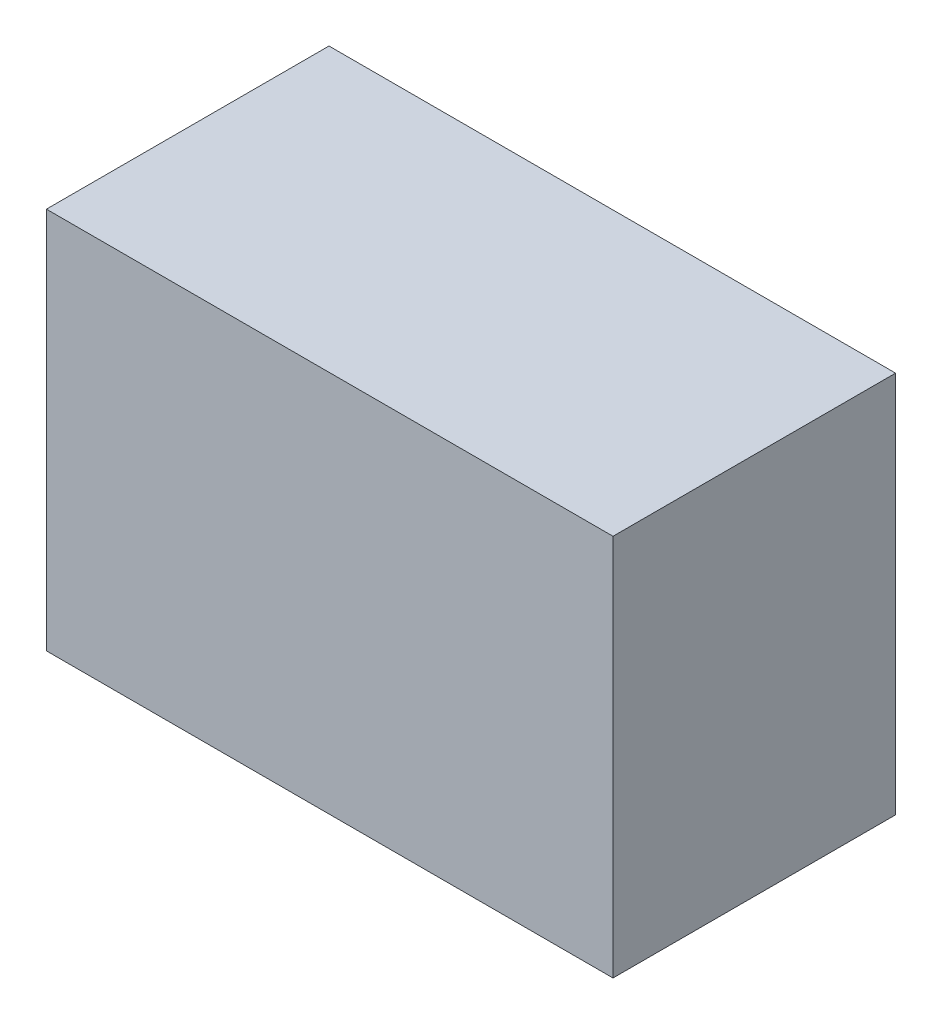
SolidWorks part; units mm, degrees
ref_plane "Front Plane" through (0, 0, 0) normal (0, 0, 1) x (1, 0, 0)
ref_plane "Top Plane" through (0, 0, 0) normal (0, 1, 0) x (1, 0, 0)
ref_plane "Right Plane" through (0, 0, 0) normal (1, 0, 0) x (0, 0, -1)
sketch "Sketch1" plane through (0, 0, 0) normal (0, 0, 1) x (1, 0, 0)
  line L0 (-1.37, -1.37) -> (6.45, -1.37)
  line L1 (6.45, -1.37) -> (6.45, 3.91)
  line L2 (6.45, 3.91) -> (-1.37, 3.91)
  line L3 (-1.37, 3.91) -> (-1.37, -1.37)
extrude "Component_Outline" add sketch "Sketch1" along normal blind 3.9 separate body
sketch3d "3DSketch1"
  line L0 (0, 0, 0) -> (1, 0, 0)
  line L1 (0, 0, 0) -> (0, 1, 0)
  line L2 (0, 0, 0) -> (0, 0, 1)
  point P0 (0, 0, 0)
